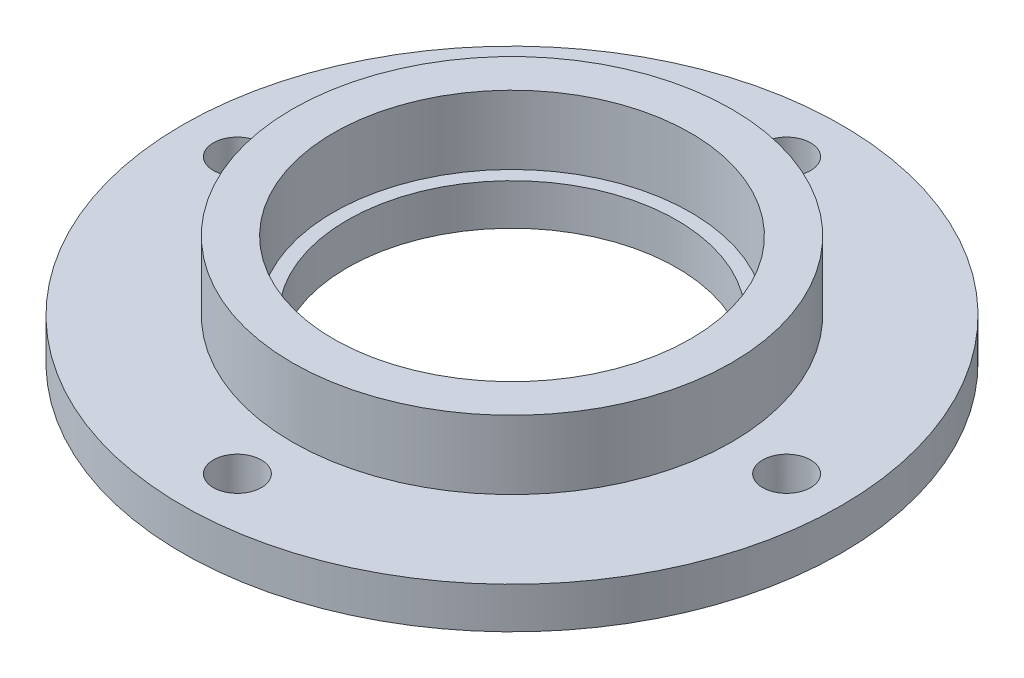
SolidWorks part; units mm, degrees
ref_plane "前视基准面" through (0, 0, 0) normal (0, 0, 1) x (1, 0, 0)
ref_plane "上视基准面" through (0, 0, 0) normal (0, 1, 0) x (1, 0, 0)
ref_plane "右视基准面" through (0, 0, 0) normal (1, 0, 0) x (0, 0, -1)
other "Configuration Table"
sketch "草图1" plane through (0, 0, 0) normal (0, 0, 1) x (1, 0, 0)
  line L0 (0, -271.3098) -> (0, 13294.181) construction
  line L1 (-12, 0) -> (-24, 0)
  line L2 (-24, 0) -> (-24, 3)
  line L3 (-24, 3) -> (-16, 3)
  line L4 (-16, 3) -> (-16, 8)
  line L5 (-16, 8) -> (-13, 8)
  line L6 (-13, 8) -> (-13, 3)
  line L7 (-13, 3) -> (-12, 3)
  line L8 (-12, 3) -> (-12, 0)
  point P5 (0, 0)
  dimension "D1" = 26
  dimension "D2" = 3
  dimension "D3" = 3
  dimension "D4" = 5
  dimension "D5" = 8
  dimension "D6" = 1
revolve "旋转1" add sketch "草图1" angle 360 about L0
sketch "草图2" plane through (0, 3, 0) normal (0, 1, 0) x (1, 0, 0)
  circle A0 centre (0, 0) radius 20 construction
  circle A1 centre (0, 20) radius 1.75
  circle A2 centre (0, 0) radius 20 construction
  circle A3 centre (20, 0) radius 1.75
  circle A4 centre (0, 0) radius 20 construction
  circle A5 centre (0, -20) radius 1.75
  circle A6 centre (0, 0) radius 20 construction
  circle A7 centre (-20, 0) radius 1.75
  point P17 (0, 0)
  dimension "D1" = 40
  dimension "D2" = 3.5
  dimension "D3" = 4
extrude "切除-拉伸1" cut sketch "草图2" against normal through all both and the other way through all
